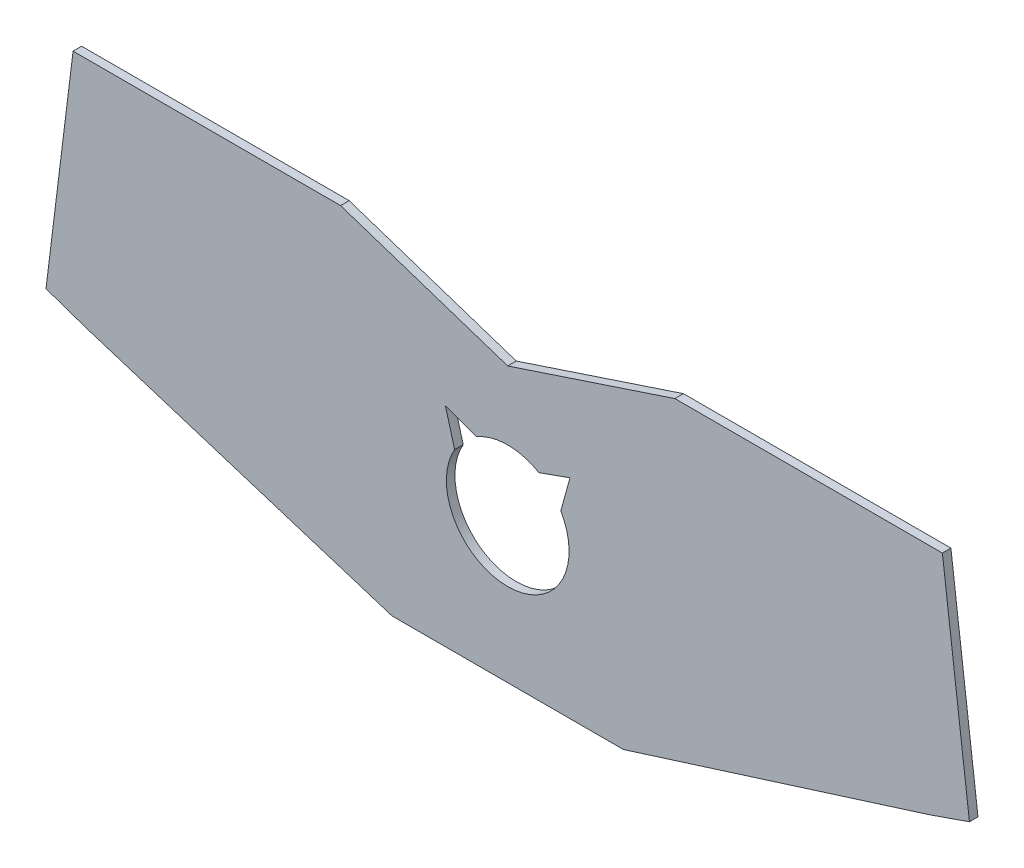
SolidWorks part; units mm, degrees
ref_plane "Спереди" through (0, 0, 0) normal (0, 0, 1) x (1, 0, 0)
ref_plane "Сверху" through (0, 0, 0) normal (0, 1, 0) x (1, 0, 0)
ref_plane "Справа" through (0, 0, 0) normal (1, 0, 0) x (0, 0, -1)
sketch "Контур" plane through (0, 0, 0) normal (0, 0, 1) x (1, 0, 0)
  line L0 (148.3547, -23.6716) -> (40.5971, -57.6623)
  line L1 (162, -18.92) -> (148.3547, -23.6716)
  line L2 (-152.5, 58) -> (-58.64, 58)
  line L4 (-10.9082, 11.6263) -> (-21.8482, 15.5133)
  line L5 (152.5, 58) -> (162, -18.92)
  line L7 (-58.64, 58) -> (0, 38.59)
  line L8 (-152.5, 58) -> (-162, -18.92)
  line L9 (58.64, 58) -> (0, 38.59)
  line L11 (-40.5971, -57.6623) -> (40.5971, -57.6623)
  line L12 (-162, -18.92) -> (-148.3547, -23.6716)
  line L14 (-148.3547, -23.6716) -> (-40.5971, -57.6623)
  line L16 (152.5, 58) -> (58.64, 58)
  line L17 (-21.8482, 15.5133) -> (-18.6176, 3.8733)
  line L18 (21.8482, 15.5133) -> (18.6176, 3.8733)
  line L19 (10.9082, 11.6263) -> (21.8482, 15.5133)
  arc A0 (10.9082, 11.6263) -> (-10.9082, 11.6263) centre (0, -6.93) ccw
  arc A3 (-18.6176, 3.8733) -> (18.6176, 3.8733) centre (0, -6.93) ccw
  point P0 (0, 0)
  point P19 (0, -57.6623)
  dimension "D1" = 43.05
  dimension "D8" = 11.64
  dimension "D11" = 45.52
sketch "Эскиз4" plane through (0, 0, 0) normal (0, 0, 1) x (1, 0, 0)
  line L0 (21.8482, 15.5133) -> (18.6176, 3.8733) construction
  line L1 (10.9082, 11.6263) -> (21.8482, 15.5133) construction
  line L2 (-10.9082, 11.6263) -> (-21.8482, 15.5133) construction
  line L3 (-21.8482, 15.5133) -> (-18.6176, 3.8733) construction
  line L4 (21.8482, 15.5133) -> (18.6176, 3.8733)
  line L5 (10.9082, 11.6263) -> (21.8482, 15.5133)
  line L6 (-10.9082, 11.6263) -> (-21.8482, 15.5133)
  line L7 (-21.8482, 15.5133) -> (-18.6176, 3.8733)
  line L12 (21.8482, 15.5133) -> (10.9082, 11.6263)
  line L13 (21.8482, 15.5133) -> (10.9082, 11.6263)
  line L14 (18.6176, 3.8733) -> (21.8482, 15.5133)
  line L15 (152.5, 58) -> (58.64, 58)
  line L16 (58.64, 58) -> (0, 38.59)
  line L17 (0, 38.59) -> (-58.64, 58)
  line L18 (-58.64, 58) -> (-152.5, 58)
  line L19 (-152.5, 58) -> (-162, -18.92)
  line L20 (-162, -18.92) -> (-148.3547, -23.6716)
  line L21 (-148.3547, -23.6716) -> (-40.5971, -57.6623)
  line L22 (18.6176, 3.8733) -> (21.8482, 15.5133)
  line L23 (-21.8482, 15.5133) -> (-18.6176, 3.8733)
  line L24 (-40.5971, -57.6623) -> (40.5971, -57.6623)
  line L25 (-21.8482, 15.5133) -> (-18.6176, 3.8733)
  line L26 (-10.9082, 11.6263) -> (-21.8482, 15.5133)
  line L27 (40.5971, -57.6623) -> (148.3547, -23.6716)
  line L28 (148.3547, -23.6716) -> (162, -18.92)
  line L29 (162, -18.92) -> (152.5, 58)
  line L30 (152.5, 58) -> (58.64, 58)
  line L31 (58.64, 58) -> (0, 38.59)
  line L32 (0, 38.59) -> (-58.64, 58)
  line L33 (-58.64, 58) -> (-152.5, 58)
  line L34 (-152.5, 58) -> (-162, -18.92)
  line L35 (-162, -18.92) -> (-148.3547, -23.6716)
  line L36 (-148.3547, -23.6716) -> (-40.5971, -57.6623)
  line L37 (-10.9082, 11.6263) -> (-21.8482, 15.5133)
  line L39 (-40.5971, -57.6623) -> (40.5971, -57.6623)
  line L42 (40.5971, -57.6623) -> (148.3547, -23.6716)
  line L43 (148.3547, -23.6716) -> (162, -18.92)
  line L44 (162, -18.92) -> (152.5, 58)
  arc A1 (10.9082, 11.6263) -> (-10.9082, 11.6263) centre (0, -6.93) ccw
  arc A2 (10.9082, 11.6263) -> (-10.9082, 11.6263) centre (0, -6.93) ccw
  arc A4 (-18.6176, 3.8733) -> (18.6176, 3.8733) centre (0, -6.93) ccw
  arc A5 (-18.6176, 3.8733) -> (18.6176, 3.8733) centre (0, -6.93) ccw
  dimension "D1" = 0
  dimension "D2" = 0
extrude "Бобышка-Вытянуть1" add sketch "Контур" along normal blind 3
